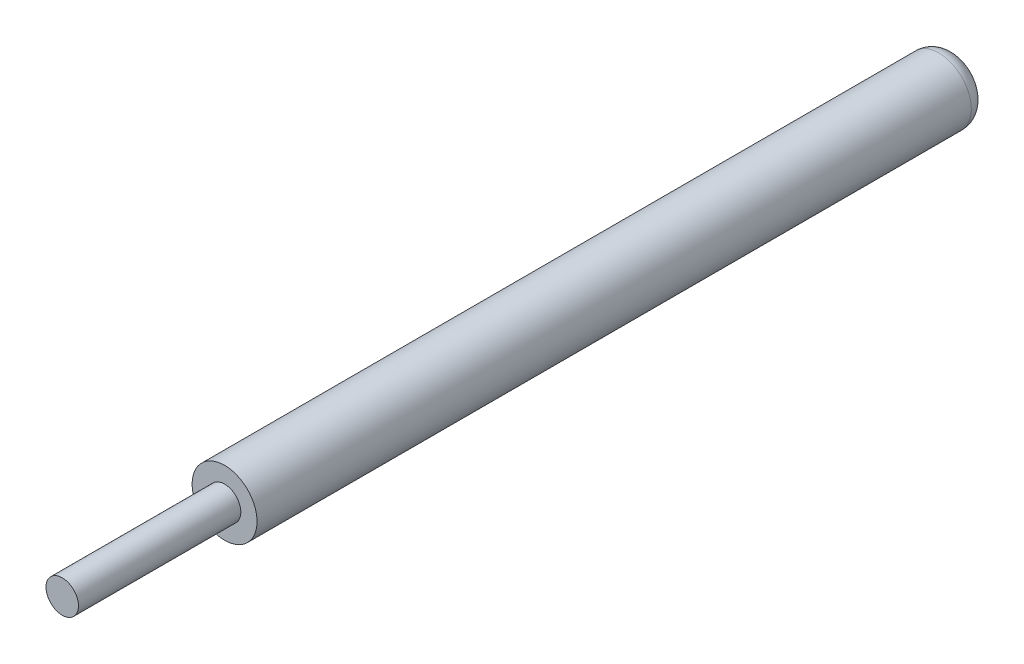
SolidWorks part; units mm, degrees
material "ASTM A36 Steel"
ref_plane "Front Plane" through (0, 0, 0) normal (0, 0, 1) x (1, 0, 0)
ref_plane "Top Plane" through (0, 0, 0) normal (0, 1, 0) x (1, 0, 0)
ref_plane "Right Plane" through (0, 0, 0) normal (1, 0, 0) x (0, 0, -1)
sketch "Sketch1" plane through (0, 0, 0) normal (1, 0, 0) x (0, 0, -1)
  line L4 (-1.27, 0.254) -> (5.715, 0.254)
  line L5 (5.715, 0.254) -> (5.715, 0)
  line L6 (5.715, 0) -> (-1.27, 0)
  line L7 (-1.27, 0) -> (-1.27, 0.254)
  line L8 (5.715, 0) -> (4.826, 0) construction
  dimension "D1" = 0.508
  dimension "D2" = 1.27
  dimension "D3" = 5.715
revolve "Revolve1" add sketch "Sketch1" angle 360 about L8
fillet "Fillet1" radius 0.127 1 edges at (0, 0.254, -5.715)
sketch "Sketch2" plane through (0, 0, 0) normal (1, 0, 0) x (0, 0, -1)
  line L0 (0, 0.508) -> (0, 0.127)
  line L1 (0, 0.127) -> (-1.6273, 0.127)
  line L2 (-1.6273, 0.127) -> (-1.6273, -0.127)
  line L3 (-1.6273, -0.127) -> (0, -0.127)
  line L4 (0, -0.127) -> (0, -0.508)
  line L5 (0, -0.508) -> (-2.032, -0.508)
  line L6 (-2.032, -0.508) -> (-2.032, 0.508)
  line L7 (-2.032, 0.508) -> (0, 0.508)
  point P2 (-1.6273, 0)
  point P9 (-2.032, 0)
  dimension "D1" = 0.254
  dimension "D2" = 2.032
  dimension "D3" = 1.016
extrude "Cut-Extrude1" [suppressed] cut sketch "Sketch2" against normal mid plane 2.54
fillet "Fillet2" [suppressed] radius 0.0508
sketch "Sketch3" plane through (0, 0, 0) normal (1, 0, 0) x (0, 0, -1)
  line L0 (-1.6189, 0) -> (-2.3287, 0) construction
  line L1 (-1.9336, 0.6099) -> (0, 0.6099)
  line L2 (-1.9336, 0.6099) -> (-1.9336, 0.127)
  line L3 (-1.9336, 0.127) -> (0, 0.127)
  line L4 (0, 0.6099) -> (0, 0.127)
  dimension "D1" = 0.254
revolve "Cut-Revolve1" cut sketch "Sketch3" angle 360 about L0
